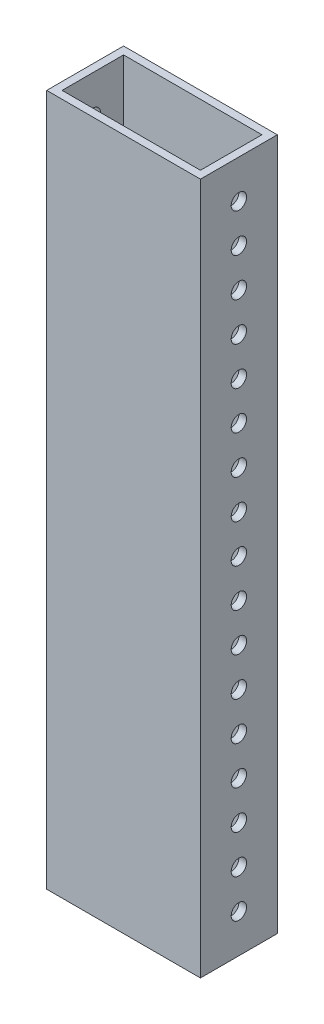
SolidWorks part; units mm, degrees
ref_plane "Front Plane" through (0, 0, 0) normal (0, 0, 1) x (1, 0, 0)
ref_plane "Top Plane" through (0, 0, 0) normal (0, 1, 0) x (1, 0, 0)
ref_plane "Right Plane" through (0, 0, 0) normal (1, 0, 0) x (0, 0, -1)
sketch "Sketch1" plane through (0, 0, 0) normal (0, 1, 0) x (1, 0, 0)
  line L1 (-47.0932, 20.4524) -> (3.7068, 20.4524)
  line L2 (-47.0932, 20.4524) -> (-47.0932, -4.9476)
  line L3 (-47.0932, -4.9476) -> (3.7068, -4.9476)
  line L4 (3.7068, 20.4524) -> (3.7068, -4.9476)
  line L5 (-47.0932, 20.4524) -> (3.7068, -4.9476) construction
  line L6 (-47.0932, -4.9476) -> (3.7068, 20.4524) construction
  line L7 (-44.5532, 17.9124) -> (1.1668, 17.9124)
  line L8 (-44.5532, 17.9124) -> (-44.5532, -2.4076)
  line L9 (-44.5532, -2.4076) -> (1.1668, -2.4076)
  line L10 (1.1668, 17.9124) -> (1.1668, -2.4076)
  line L11 (-44.5532, 17.9124) -> (1.1668, -2.4076) construction
  line L12 (-44.5532, -2.4076) -> (1.1668, 17.9124) construction
  point P0 (-21.6932, 7.7524)
  point P5 (-21.6932, 7.7524)
  dimension "D1" = 2.54
  dimension "D2" = 2.54
  dimension "D3" = 2.54
  dimension "D4" = 2.54
  dimension "D5" = 25.4
  dimension "D6" = 50.8
extrude "Boss-Extrude1" add sketch "Sketch1" along normal blind 228.6
sketch "Sketch2" plane through (3.7068, 0, 0) normal (1, 0, 0) x (0, 0, -1)
  line L0 (-4.9476, 228.6) -> (20.4524, 228.6) construction
  line L1 (20.4524, 228.6) -> (20.4524, 0) construction
  circle A0 centre (7.7524, 215.9) radius 2.54
  circle A1 centre (7.7524, 203.2) radius 2.54
  circle A2 centre (7.7524, 190.5) radius 2.54
  circle A3 centre (7.7524, 177.8) radius 2.54
  circle A4 centre (7.7524, 165.1) radius 2.54
  circle A5 centre (7.7524, 152.4) radius 2.54
  circle A6 centre (7.7524, 139.7) radius 2.54
  circle A7 centre (7.7524, 127) radius 2.54
  circle A8 centre (7.7524, 114.3) radius 2.54
  circle A9 centre (7.7524, 101.6) radius 2.54
  circle A10 centre (7.7524, 88.9) radius 2.54
  circle A11 centre (7.7524, 76.2) radius 2.54
  circle A12 centre (7.7524, 63.5) radius 2.54
  circle A13 centre (7.7524, 50.8) radius 2.54
  circle A14 centre (7.7524, 38.1) radius 2.54
  circle A15 centre (7.7524, 25.4) radius 2.54
  circle A16 centre (7.7524, 12.7) radius 2.54
  dimension "D3" = 5.08
  dimension "D1" = 12.7
  dimension "D2" = 12.7
  dimension "D4" = 17
extrude "Cut-Extrude2" cut sketch "Sketch2" against normal blind 228.6
